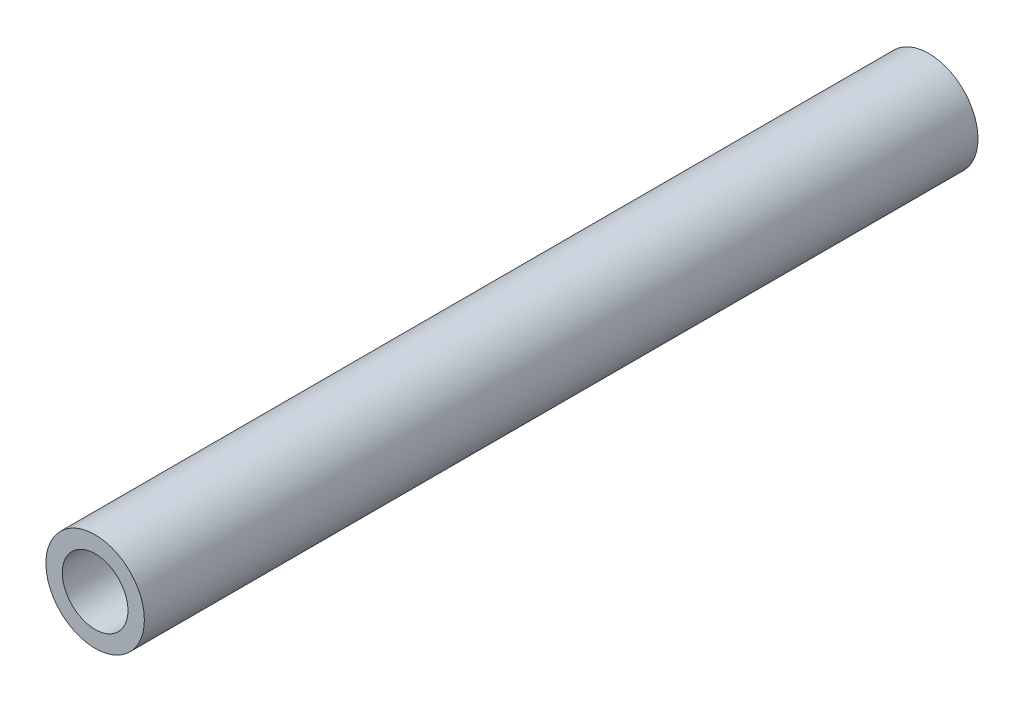
SolidWorks part; units mm, degrees
ref_plane "Front Plane" through (0, 0, 0) normal (0, 0, 1) x (1, 0, 0)
ref_plane "Top Plane" through (0, 0, 0) normal (0, 1, 0) x (1, 0, 0)
ref_plane "Right Plane" through (0, 0, 0) normal (1, 0, 0) x (0, 0, -1)
sketch "Sketch1" plane through (0, 0, 0) normal (0, 0, 1) x (1, 0, 0)
  circle A0 centre (0, 0) radius 3
  circle A1 centre (0, 0) radius 2
  dimension "D1" = 6
  dimension "D2" = 4
extrude "Boss-Extrude1" add sketch "Sketch1" along normal blind 50.8
